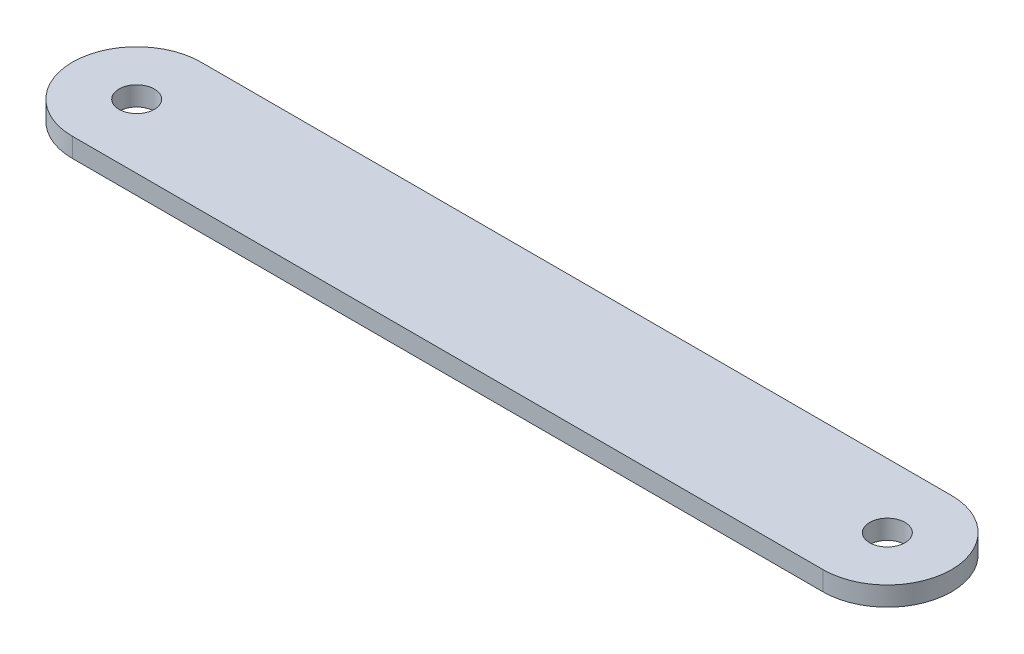
SolidWorks part; units mm, degrees
ref_plane "前视基准面" through (0, 0, 0) normal (0, 0, 1) x (1, 0, 0)
ref_plane "上视基准面" through (0, 0, 0) normal (0, 1, 0) x (1, 0, 0)
ref_plane "右视基准面" through (0, 0, 0) normal (1, 0, 0) x (0, 0, -1)
sketch "草图1" plane through (0, 0, 0) normal (0, 1, 0) x (1, 0, 0)
  line L0 (116.85, 0) -> (-116.85, 0) construction
  line L2 (116.85, -20) -> (-116.85, -20)
  line L3 (116.85, 20) -> (-116.85, 20)
  arc A0 (116.85, -20) -> (116.85, 20) centre (116.85, 0) ccw
  arc A1 (-116.85, 20) -> (-116.85, -20) centre (-116.85, 0) ccw
  point P5 (0, 0)
  dimension "D2" = 20
  dimension "D1" = 233.7
extrude "凸台-拉伸1" add sketch "草图1" along normal mid plane 6
sketch "草图2" plane through (0, 3, 0) normal (0, 1, 0) x (1, 0, 0)
  line L0 (0, 0) -> (0, 48.1422) construction
  circle A0 centre (-116.85, 0) radius 5.5
  circle A2 centre (116.85, 0) radius 5.5
  point P2 (0, 0)
  dimension "D1" = 11
  dimension "D2" = 233.7
extrude "切除-拉伸1" cut sketch "草图2" against normal blind 9
